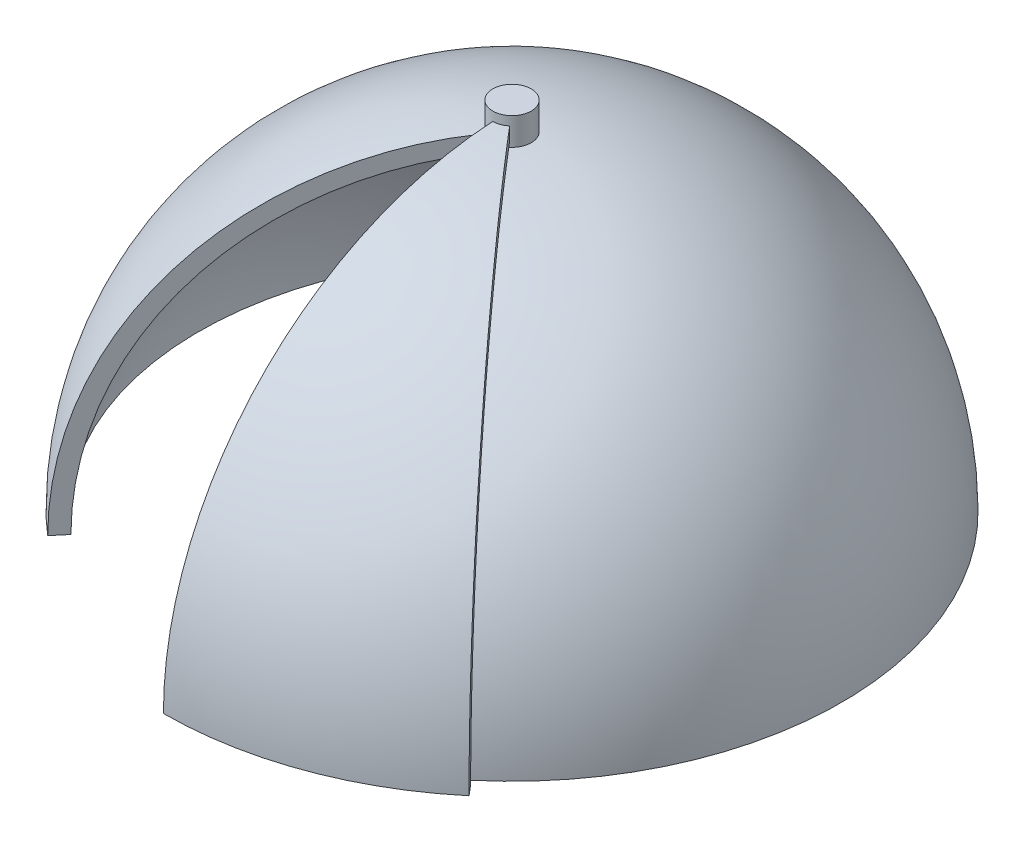
SolidWorks part; units mm, degrees
ref_plane "Front" through (0, 0, 0) normal (0, 0, 1) x (1, 0, 0)
ref_plane "Top" through (0, 0, 0) normal (0, 1, 0) x (1, 0, 0)
ref_plane "Right" through (0, 0, 0) normal (1, 0, 0) x (0, 0, -1)
sketch "Sketch1" plane through (0, 0, 0) normal (1, 0, 0) x (0, 0, -1)
  line L2 (0, 11400) -> (0, 12000)
  line L3 (-11400, 0) -> (-12000, 0)
  arc A0 (0, 12000) -> (-12000, 0) centre (0, 0) ccw
  arc A1 (0, 11400) -> (-11400, 0) centre (0, 0) ccw
revolve "Revolve1" add sketch "Sketch1" angle 320 about L2
sketch "Sketch2" plane through (0, 0, 0) normal (1, 0, 0) x (0, 0, -1)
  line L0 (-12210.978, 0) -> (-12693.1419, 0)
  line L1 (0, 12210.978) -> (0, 12693.1419)
  arc A0 (0, 12693.1419) -> (-12693.1419, 0) centre (0, 0) ccw
  arc A1 (0, 12210.978) -> (-12210.978, 0) centre (0, 0) ccw
revolve "Revolve2" add sketch "Sketch2" angle 40 about L1
ref_plane "Plane1" through (0, 12000, 0) normal (0, 1, 0) x (1, 0, 0)
sketch "Sketch3" plane through (0, 12000, 0) normal (0, 1, 0) x (1, 0, 0)
  circle A0 centre (0, 0) radius 700
extrude "Boss-Extrude1" add sketch "Sketch3" along normal blind 1000
